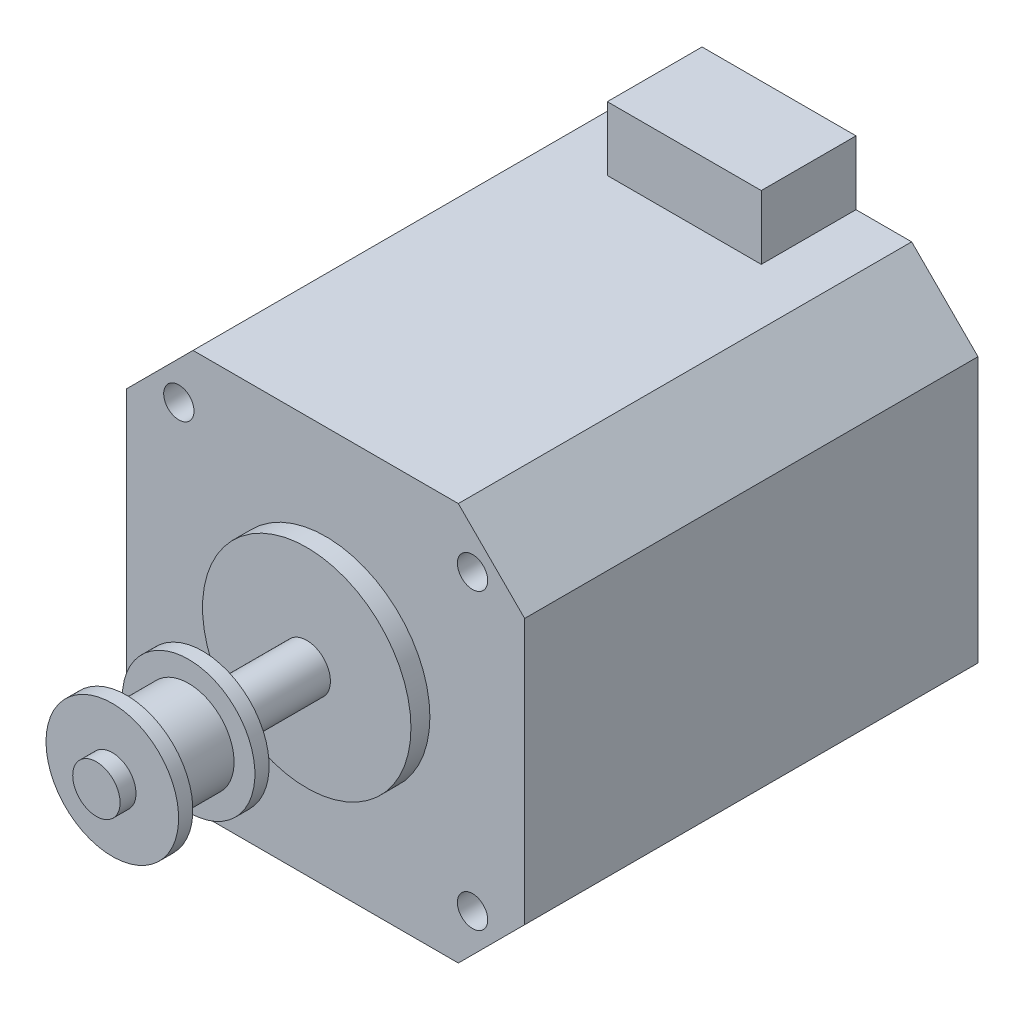
SolidWorks part; units mm, degrees
ref_plane "Front Plane" through (0, 0, 0) normal (0, 0, 1) x (1, 0, 0)
ref_plane "Top Plane" through (0, 0, 0) normal (0, 1, 0) x (1, 0, 0)
ref_plane "Right Plane" through (0, 0, 0) normal (1, 0, 0) x (0, 0, -1)
sketch "Sketch1" plane through (0, 0, 0) normal (0, 0, 1) x (1, 0, 0)
  line L1 (0, 0) -> (42, 0)
  line L2 (0, 0) -> (0, 42)
  line L3 (0, 42) -> (42, 42)
  line L4 (42, 0) -> (42, 42)
  dimension "D1" = 42
  dimension "D2" = 42
extrude "Boss-Extrude1" add sketch "Sketch1" along normal blind 47.85
chamfer "Chamfer1" distance 7 angle 45 4 edges at (0, 0, 23.925) (42, 0, 23.925) (42, 42, 23.925) (0, 42, 23.925)
sketch "Sketch2" plane through (0, 0, 47.85) normal (0, 0, 1) x (1, 0, 0)
  line L0 (21, 42) -> (21, 16.3148) construction
  line L1 (35, 42) -> (7, 42) construction
  line L2 (0, 21) -> (29.4511, 21) construction
  line L3 (0, 35) -> (0, 7) construction
  circle A0 centre (21, 21) radius 11
  dimension "D1" = 22
extrude "Boss-Extrude2" add sketch "Sketch2" along normal blind 2
sketch "Sketch3" plane through (0, 0, 0) normal (0, 0, -1) x (-1, 0, 0)
  line L0 (-35, 42) -> (-7, 42) construction
  line L1 (-29.125, 42) -> (-12.875, 42)
  line L2 (-29.125, 42) -> (-29.125, 48.75)
  line L3 (-29.125, 48.75) -> (-12.875, 48.75)
  line L4 (-12.875, 42) -> (-12.875, 48.75)
  line L5 (-21, 0) -> (-21, 6.0549) construction
  line L6 (-7, 0) -> (-35, 0) construction
  point P10 (-21, 48.75)
  dimension "D1" = 16.25
  dimension "D2" = 6.75
extrude "Boss-Extrude3" add sketch "Sketch3" against normal blind 10
sketch "Sketch4" plane through (0, 0, 47.85) normal (0, 0, 1) x (1, 0, 0)
  line L0 (0, 21) -> (6.2344, 21) construction
  line L1 (0, 35) -> (0, 7) construction
  line L2 (21, 42) -> (21, 37.0411) construction
  line L3 (29.125, 42) -> (12.875, 42) construction
  circle A0 centre (5.5, 36.5) radius 1.6
  circle A1 centre (36.5, 36.5) radius 1.6
  circle A2 centre (36.5, 5.5) radius 1.6
  circle A3 centre (5.5, 5.5) radius 1.6
  dimension "D5" = 3.2
  dimension "D1" = 31
  dimension "D2" = 15.5
  dimension "D3" = 15.5
  dimension "D4" = 31
extrude "Cut-Extrude1" cut sketch "Sketch4" against normal blind 3
ref_plane "Plane1" through (0, 21, 0) normal (0, -1, 0) x (-1, 0, 0)
sketch "Sketch5" plane through (0, 21, 0) normal (0, -1, 0) x (-1, 0, 0)
  line L0 (-21, -49.85) -> (-21, -72.05)
  line L1 (-32, -49.85) -> (-10, -49.85) construction
  line L2 (-16.2, -68.87) -> (-14, -68.87)
  line L3 (-21, -70.37) -> (-14, -70.37)
  line L4 (-14, -70.37) -> (-14, -68.87)
  line L5 (-16.2, -68.87) -> (-16.2, -62.32)
  line L6 (-16.2, -62.32) -> (-14, -62.32)
  line L7 (-14, -62.32) -> (-14, -60.82)
  line L8 (-14, -60.82) -> (-21, -60.82)
  line L9 (-18.5, -49.85) -> (-18.5, -72.05)
  line L10 (-18.5, -72.05) -> (-21, -72.05)
  line L11 (-21, -49.85) -> (-18.5, -49.85)
  dimension "D1" = 22.2
  dimension "D2" = 7
  dimension "D3" = 1.68
  dimension "1.5" = 1.5
  dimension "D4" = 6.55
  dimension "D5" = 1.5
  dimension "D6" = 4.8
  dimension "D7" = 2.5
revolve "Revolve1" add sketch "Sketch5" angle 360 about L0
